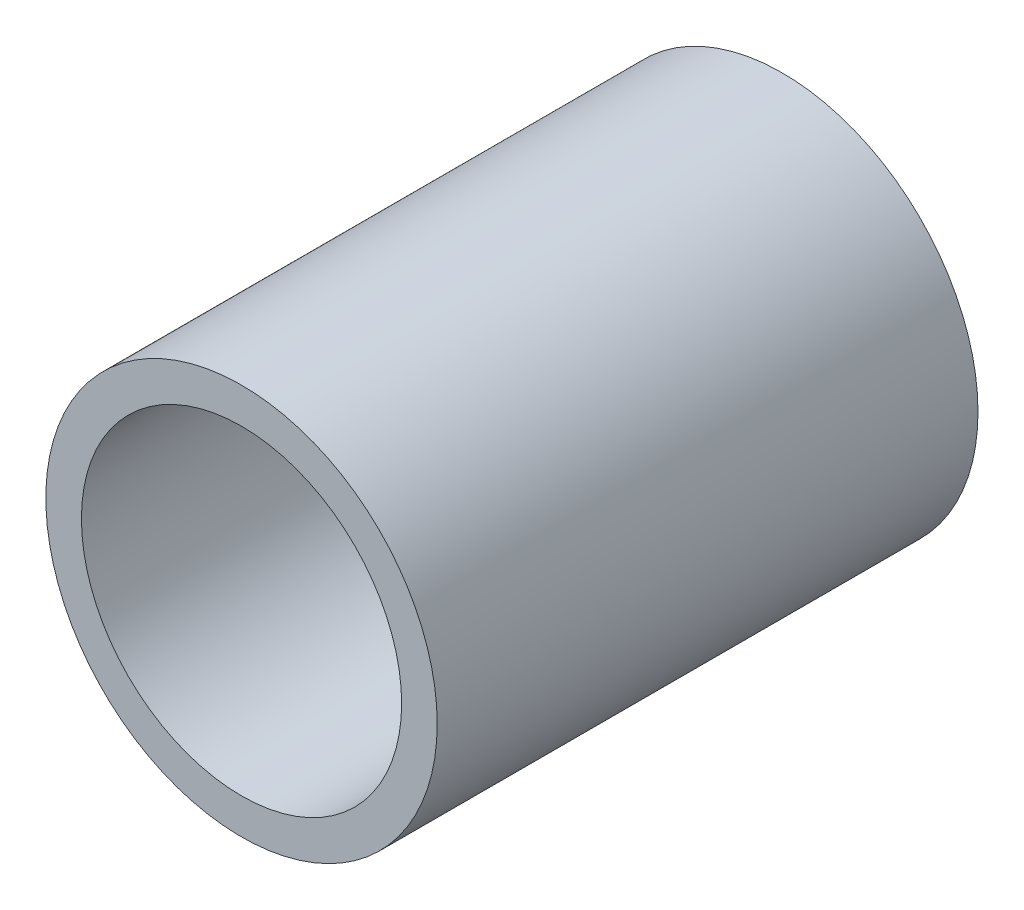
SolidWorks part; units mm, degrees
ref_plane "Front Plane" through (0, 0, 0) normal (0, 0, 1) x (1, 0, 0)
ref_plane "Top Plane" through (0, 0, 0) normal (0, 1, 0) x (1, 0, 0)
ref_plane "Right Plane" through (0, 0, 0) normal (1, 0, 0) x (0, 0, -1)
sketch "Sketch1" plane through (0, 0, 0) normal (0, 0, 1) x (1, 0, 0)
  circle A0 centre (0, 0) radius 2.25
  circle A1 centre (0, 0) radius 2.75
  dimension "D1" = 4.5
  dimension "D2" = 5.5
extrude "Boss-Extrude1" add sketch "Sketch1" against normal blind 7.6
scale "Scale1" scale about origin uniform scaling yes scale factor 1.5
